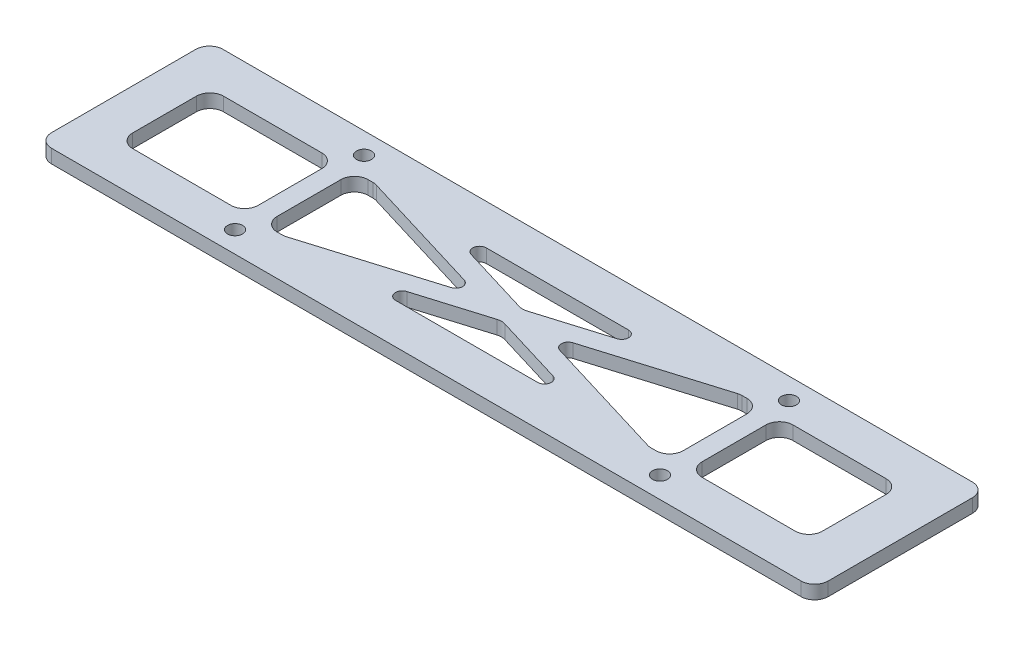
SolidWorks part; units mm, degrees
ref_plane "Front Plane" through (0, 0, 0) normal (0, 0, 1) x (1, 0, 0)
ref_plane "Top Plane" through (0, 0, 0) normal (0, 1, 0) x (1, 0, 0)
ref_plane "Right Plane" through (0, 0, 0) normal (1, 0, 0) x (0, 0, -1)
sketch "Sketch1" plane through (0, 0, 0) normal (0, 1, 0) x (1, 0, 0)
  line L0 (6.6978, 14.7554) -> (6.6978, 57.6447) construction
  line L1 (-65.8065, -1.2466) -> (79.2021, -1.2466)
  line L2 (-65.8065, -1.2466) -> (-65.8065, 30.7574)
  line L3 (-65.8065, 30.7574) -> (79.2021, 30.7574)
  line L4 (79.2021, -1.2466) -> (79.2021, 30.7574)
  line L5 (6.6978, 14.7554) -> (101.7039, 14.7554) construction
  line L6 (-32.9781, 26.795) -> (46.3737, 2.7158) construction
  line L7 (46.3737, 2.7158) -> (46.3737, 26.795) construction
  line L8 (46.3737, 26.795) -> (-32.9781, 2.7158) construction
  line L9 (-32.9781, 2.7158) -> (-32.9781, 26.795) construction
  line L10 (-32.9781, 26.795) -> (46.3737, 26.795) construction
  line L11 (-32.9781, 2.7158) -> (46.3737, 2.7158) construction
  line L12 (-32.9781, 2.7158) -> (-61.7425, 2.7158) construction
  line L13 (-61.7425, 2.7158) -> (-61.7425, 26.795) construction
  line L14 (-61.7425, 26.795) -> (-32.9781, 26.795) construction
  line L15 (46.3737, 26.795) -> (74.1651, 26.795) construction
  line L16 (74.1651, 26.795) -> (74.1651, 2.7158) construction
  line L17 (74.1651, 2.7158) -> (46.3737, 2.7158) construction
  line L18 (-31.2001, 23.239) -> (-27.3826, 23.239)
  line L19 (48.1517, 23.239) -> (70.6091, 23.239)
  line L20 (70.6091, 23.239) -> (70.6091, 6.2718)
  line L21 (70.6091, 6.2718) -> (48.1517, 6.2718)
  line L22 (-31.2001, 6.2718) -> (-27.3826, 6.2718)
  line L23 (-34.7561, 6.2718) -> (-58.1865, 6.2718)
  line L24 (-58.1865, 6.2718) -> (-58.1865, 23.239)
  line L25 (-58.1865, 23.239) -> (-34.7561, 23.239)
  line L26 (-32.4618, 28.4964) -> (46.89, 4.4172) construction
  line L27 (40.7782, 23.239) -> (12.8209, 14.7554)
  line L28 (-15.1363, 23.239) -> (6.6978, 16.6134)
  line L30 (44.5957, 6.2718) -> (44.5957, 23.239)
  line L31 (48.1517, 6.2718) -> (48.1517, 23.239)
  line L32 (-34.7561, 6.2718) -> (-34.7561, 23.239)
  line L33 (40.7782, 6.2718) -> (44.5957, 6.2718)
  line L34 (-34.7561, 2.7158) -> (-34.7561, 26.795) construction
  line L35 (-58.1865, 23.239) -> (-32.9781, 23.239) construction
  line L36 (-32.9781, 23.239) -> (46.3737, 23.239) construction
  line L37 (-15.1363, 23.239) -> (28.5319, 23.239)
  line L38 (70.6091, 6.2718) -> (46.3737, 6.2718) construction
  line L39 (-27.3826, 23.239) -> (0.5747, 14.7554)
  line L40 (0.5747, 14.7554) -> (-27.3826, 6.2718)
  line L42 (6.6978, 12.8973) -> (-15.1363, 6.2718)
  line L44 (6.6978, 12.8973) -> (28.5319, 6.2718)
  line L45 (12.8209, 14.7554) -> (40.7782, 6.2718)
  line L46 (48.1517, 2.7158) -> (48.1517, 26.795) construction
  line L47 (-31.2001, 6.2718) -> (-31.2001, 23.239)
  line L48 (-15.1363, 6.2718) -> (28.5319, 6.2718)
  line L49 (-32.9781, 6.2718) -> (46.3737, 6.2718) construction
  line L50 (-32.9781, 6.2718) -> (-58.1865, 6.2718) construction
  line L51 (28.5319, 23.239) -> (6.6978, 16.6134)
  line L52 (40.7782, 23.239) -> (44.5957, 23.239)
  line L53 (46.3737, 23.239) -> (70.6091, 23.239) construction
  line L54 (-27.3826, 23.239) -> (-27.3826, 6.2718) construction
  line L56 (40.7782, 23.239) -> (40.7782, 6.2718) construction
  line L57 (28.5319, 23.239) -> (28.5319, 6.2718) construction
  line L58 (-15.1363, 23.239) -> (-15.1363, 6.2718) construction
  circle A0 centre (-32.9781, 26.795) radius 1.4
  circle A1 centre (46.3737, 26.795) radius 1.4
  circle A2 centre (46.3737, 2.7158) radius 1.4
  circle A3 centre (-32.9781, 2.7158) radius 1.4
  point P0 (6.6978, 14.7554)
  dimension "D3" = 2.8
  dimension "D15" = 3.9624
  dimension "D1" = 145.0086
  dimension "D2" = 32.004
  dimension "D4" = 3.9624
  dimension "D5" = 32.8284
  dimension "D6" = 4.064
  dimension "D7" = 3.9624
  dimension "D8" = 5.037
  dimension "D10" = 7.62
  dimension "D14" = 7.5184
  dimension "D16" = 3.9624
  dimension "D17" = 3.556
  dimension "D18" = 16.9672
  dimension "D19" = 23.4304
  dimension "D20" = 3.8175
  dimension "D21" = 3.8175
  dimension "D22" = 3.556
  dimension "D9" = 3.556
  dimension "D11" = 1.778
  dimension "D12" = 1.778
  dimension "D13" = 1.778
extrude "Boss-Extrude1" add sketch "Sketch1" along normal blind 2.54
fillet "Fillet1" radius 2.54 22 edges at (-65.8065, 1.27, -30.7574) (79.2021, 1.27, -30.7574) (79.2021, 1.27, 1.2466) (-65.8065, 1.27, 1.2466) (40.7782, 1.27, -6.2718) (44.5957, 1.27, -6.2718) (70.6091, 1.27, -6.2718) (48.1517, 1.27, -6.2718) (70.6091, 1.27, -23.239) (44.5957, 1.27, -23.239) (40.7782, 1.27, -23.239) (48.1517, 1.27, -23.239) (6.6978, 1.27, -16.6134) (6.6978, 1.27, -12.8973) (-58.1865, 1.27, -23.239) (-31.2001, 1.27, -23.239) (-27.3826, 1.27, -23.239) (-34.7561, 1.27, -23.239) (-27.3826, 1.27, -6.2718) (-34.7561, 1.27, -6.2718) (-31.2001, 1.27, -6.2718) (-58.1865, 1.27, -6.2718)
fillet "Fillet2" radius 1.27 6 edges at (28.5319, 1.27, -6.2718) (-15.1363, 1.27, -6.2718) (-15.1363, 1.27, -23.239) (28.5319, 1.27, -23.239) (0.5747, 1.27, -14.7554) (12.8209, 1.27, -14.7554)
